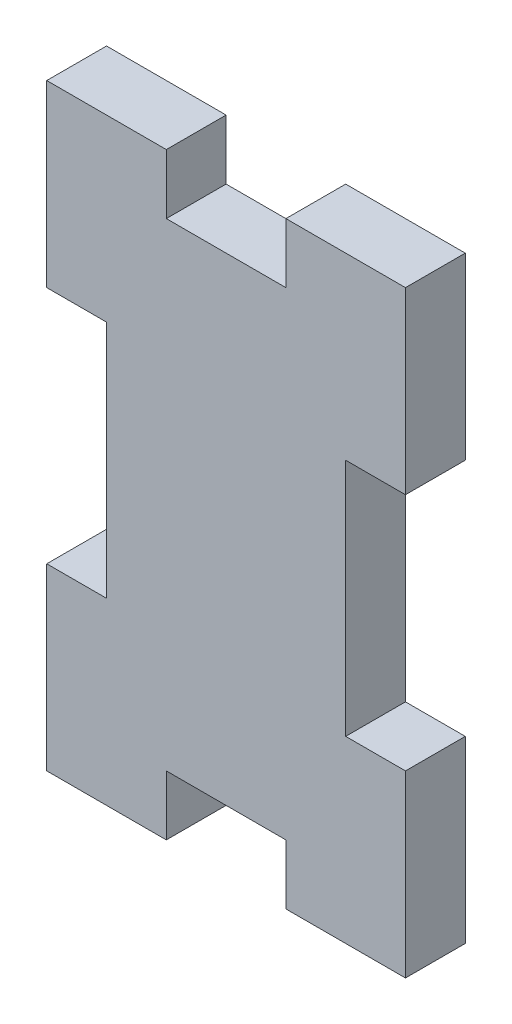
SolidWorks part; units mm, degrees
ref_plane "Front Plane" through (0, 0, 0) normal (0, 0, 1) x (1, 0, 0)
ref_plane "Top Plane" through (0, 0, 0) normal (0, 1, 0) x (1, 0, 0)
ref_plane "Right Plane" through (0, 0, 0) normal (1, 0, 0) x (0, 0, -1)
sketch "Sketch1" plane through (0, 0, 0) normal (0, 0, 1) x (1, 0, 0)
  line L32 (12.999, 15.5153) -> (12.999, 5.5153)
  line L33 (12.999, 5.5153) -> (17.999, 5.5153)
  line L37 (22.999, 15.5153) -> (22.999, 20.5153)
  line L38 (22.999, 20.5153) -> (12.999, 20.5153)
  line L39 (12.999, 20.5153) -> (12.999, 15.5153)
  line L41 (42.999, 15.5153) -> (42.999, 20.5153)
  line L42 (42.999, 20.5153) -> (32.999, 20.5153)
  line L43 (32.999, 20.5153) -> (32.999, 15.5153)
  line L45 (37.999, 5.5153) -> (42.999, 5.5153)
  line L46 (42.999, 5.5153) -> (42.999, 15.5153)
  line L50 (42.999, -24.4847) -> (42.999, -14.4847)
  line L51 (42.999, -14.4847) -> (37.999, -14.4847)
  line L52 (32.999, -29.4847) -> (42.999, -29.4847)
  line L53 (42.999, -29.4847) -> (42.999, -24.4847)
  line L55 (32.999, -24.4847) -> (32.999, -29.4847)
  line L56 (12.999, -29.4847) -> (22.999, -29.4847)
  line L57 (22.999, -29.4847) -> (22.999, -24.4847)
  line L59 (12.999, -24.4847) -> (12.999, -29.4847)
  line L60 (12.999, -14.4847) -> (12.999, -24.4847)
  line L63 (17.999, -14.4847) -> (12.999, -14.4847)
  line L64 (17.999, -14.4847) -> (17.999, 5.5153)
  line L65 (22.999, 15.5153) -> (32.999, 15.5153)
  line L66 (37.999, 5.5153) -> (37.999, -14.4847)
  line L67 (32.999, -24.4847) -> (22.999, -24.4847)
extrude "Boss-Extrude1" add sketch "Sketch1" along normal blind 5
